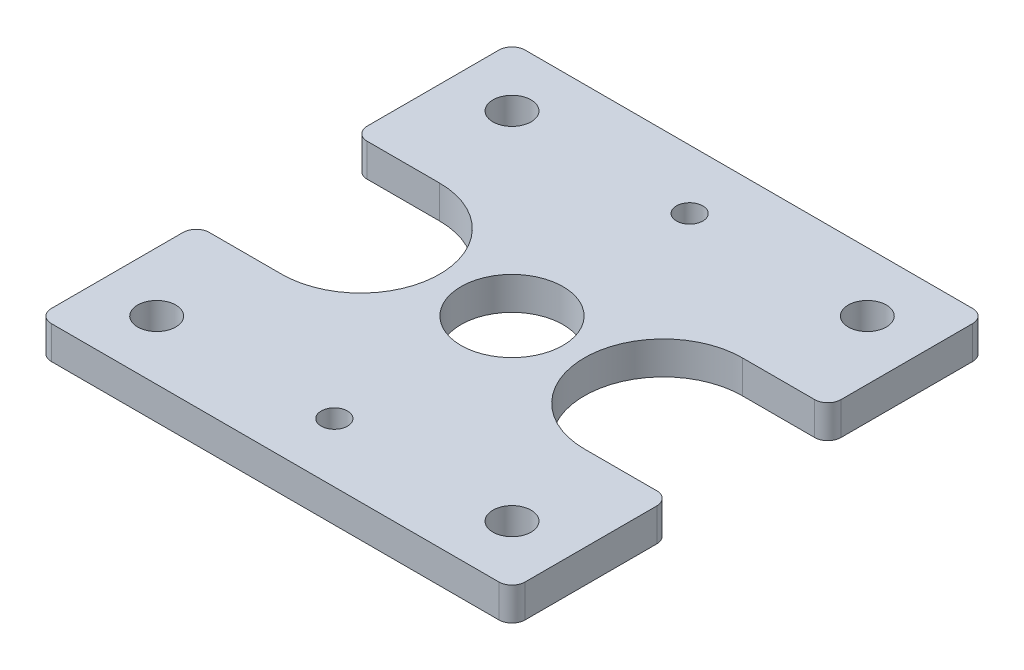
SolidWorks part; units mm, degrees
ref_plane "Front Plane" through (0, 0, 0) normal (0, 0, 1) x (1, 0, 0)
ref_plane "Top Plane" through (0, 0, 0) normal (0, 1, 0) x (1, 0, 0)
ref_plane "Right Plane" through (0, 0, 0) normal (1, 0, 0) x (0, 0, -1)
sketch "Sketch2" plane through (0, 0, 0) normal (0, 1, 0) x (1, 0, 0)
  line L0 (-36, 12) -> (-36, 36)
  line L1 (-36, -36) -> (36, -36)
  line L2 (-36, -36) -> (-36, -12)
  line L3 (-36, 36) -> (36, 36)
  line L4 (36, -36) -> (36, -12)
  line L5 (-36, -36) -> (36, 36) construction
  line L6 (-36, 36) -> (36, -36) construction
  line L7 (36, 12) -> (36, 36)
  line L8 (-23, 12) -> (-36, 12)
  line L9 (-23, -12) -> (-36, -12)
  line L10 (23, 12) -> (36, 12)
  line L11 (23, -12) -> (36, -12)
  circle A0 centre (0, 0) radius 7.75
  circle A1 centre (-27, 27) radius 2.9
  circle A2 centre (27, 27) radius 2.9
  circle A3 centre (27, -27) radius 2.9
  circle A4 centre (-27, -27) radius 2.9
  arc A6 (23, 12) -> (23, -12) centre (23, 0) ccw
  arc A7 (-23, -12) -> (-23, 12) centre (-23, 0) ccw
  circle A8 centre (0, -27) radius 2
  circle A9 centre (0, 27) radius 2
  point P0 (0, 0)
  dimension "D1" = 15.5
  dimension "D4" = 5.8
  dimension "D8" = 9
  dimension "D9" = 24
  dimension "D10" = 13
  dimension "D11" = 13
  dimension "D12" = 24
  dimension "D13" = 4
  dimension "D14" = 4
  dimension "D2" = 72
  dimension "D3" = 72
extrude "Boss-Extrude1" add sketch "Sketch2" along normal blind 5
fillet "Fillet1" radius 2 4 edges at (36, 2.5, -36) (-36, 2.5, -36) (36, 2.5, 36) (-36, 2.5, 36)
fillet "Fillet2" radius 2 4 edges at (-36, 2.5, -12) (-36, 2.5, 12) (36, 2.5, 12) (36, 2.5, -12)
